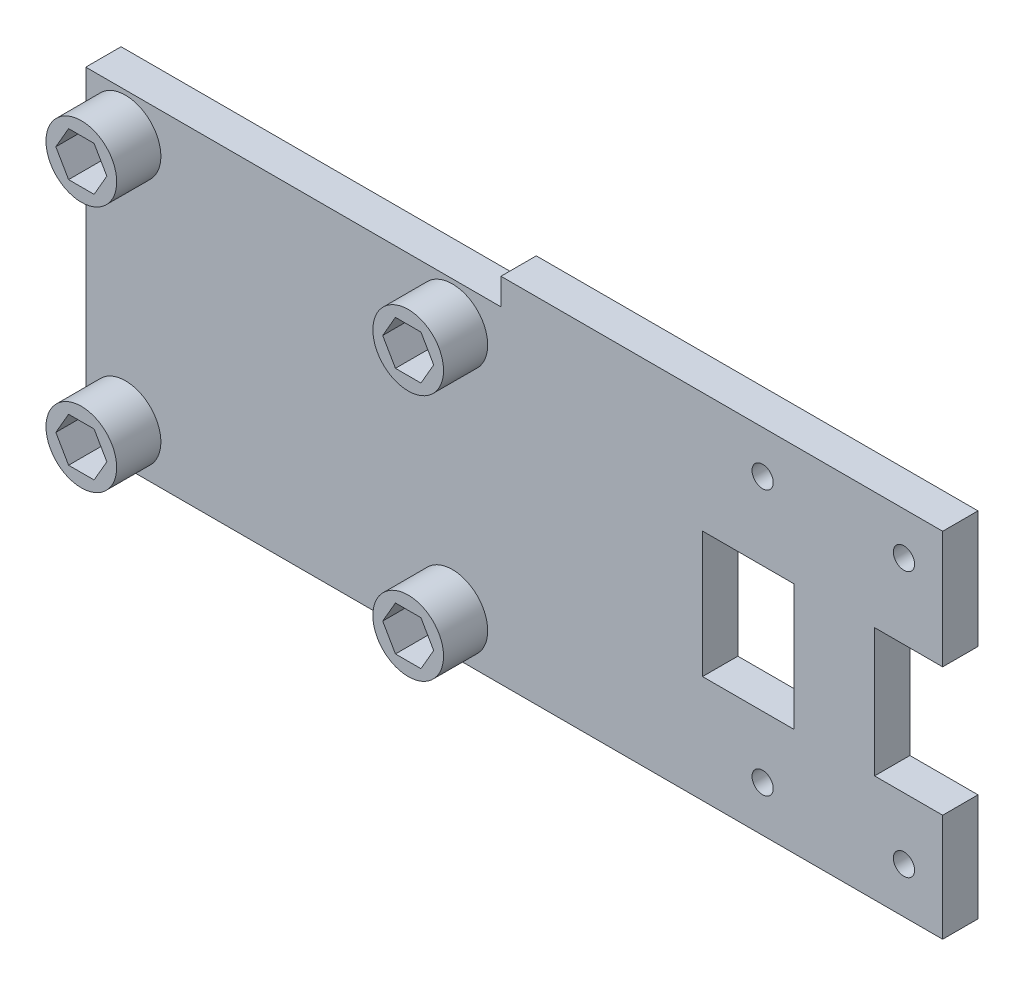
SolidWorks part; units mm, degrees
ref_plane "Front Plane" through (0, 0, 0) normal (0, 0, 1) x (1, 0, 0)
ref_plane "Top Plane" through (0, 0, 0) normal (0, 1, 0) x (1, 0, 0)
ref_plane "Right Plane" through (0, 0, 0) normal (1, 0, 0) x (0, 0, -1)
ref_plane "Plane1" through (0, 0, 34.8116) normal (0, 0, -1) x (-1, 0, 0)
sketch "Sketch1" plane through (0, 0, 34.8116) normal (0, 0, -1) x (-1, 0, 0)
  line L0 (-23.5355, 118.8347) -> (-23.5355, 78.8347)
  line L1 (-23.5355, 78.8347) -> (26.4645, 78.8347)
  line L2 (26.4645, 78.8347) -> (26.4645, 118.8347)
  line L3 (26.4645, 118.8347) -> (-23.5355, 118.8347)
extrude "Boss-Extrude1" add sketch "Sketch1" against normal blind 4
sketch "Sketch2" plane through (0, 0, 38.8116) normal (0, 0, 1) x (1, 0, 0)
  line L0 (23.5355, 90.9981) -> (23.5355, 105.5372)
  line L1 (23.5355, 105.5372) -> (15.8296, 105.5372)
  line L2 (15.8296, 105.5372) -> (15.8296, 90.9981)
  line L3 (15.8296, 90.9981) -> (23.5355, 90.9981)
extrude "Cut-Extrude1" cut sketch "Sketch2" against normal through all
sketch "Sketch3" plane through (0, 0, 38.8116) normal (0, 0, 1) x (1, 0, 0)
  line L0 (6.7257, 105.2654) -> (-3.6465, 105.2654)
  line L1 (-3.6465, 105.2654) -> (-3.6465, 90.9981)
  line L2 (-3.6465, 90.9981) -> (6.7257, 90.9981)
  line L3 (6.7257, 90.9981) -> (6.7257, 105.2654)
extrude "Cut-Extrude2" cut sketch "Sketch3" against normal through all
hole_wizard "CBORE for M2 Pan Head Machine Screw1" positions "Sketch5" profile "Sketch4" counterbore size "M2" standard "ANSI Metric" end condition up to next
sketch "Sketch5" plane through (0, 0, 34.8116) normal (0, 0, -1) x (-1, 0, 0)
  point P0 (-3.1566, 84.0163)
  point P1 (-19.1566, 84.0163)
  point P2 (-19.1566, 114.0163)
  point P3 (-3.1566, 114.0163)
sketch "Sketch4" plane through (3.1566, 84.0163, 34.8116) normal (1, 0, 0) x (0, 1, 0)
  line L0 (0, 0) -> (0, 4)
  line L1 (0, 4) -> (1.2, 4)
  line L3 (1.2, 4) -> (1.2, 1.6)
  line L4 (1.2, 1.6) -> (2.5, 1.6)
  line L5 (2.5, 1.6) -> (2.5, 0)
  line L7 (2.5, 0) -> (0, 0)
  line L11 (0, -6.35) -> (0, 107.95) construction
  dimension "Thru Hole Dia." = 2.4
  dimension "Thru Hole Depth" = 4
  dimension "C'Bore Dia." = 5
  dimension "C'Bore Depth" = 1.6
sketch "Sketch6" plane through (0, 0, 38.8116) normal (0, 0, 1) x (1, 0, 0)
  line L1 (-26.4645, 78.8347) -> (-73.4645, 78.8347)
  line L2 (-26.4645, 78.8347) -> (-26.4645, 115.8347)
  line L3 (-26.4645, 115.8347) -> (-73.4645, 115.8347)
  line L4 (-73.4645, 78.8347) -> (-73.4645, 115.8347)
  dimension "D1" = 47
  dimension "D2" = 37
extrude "Boss-Extrude2" add sketch "Sketch6" against normal up to surface (4 mm away) up to face at (0.6566, 84.0163, 34.8116)
sketch "Sketch7" plane through (0, 0, 38.8116) normal (0, 0, 1) x (1, 0, 0)
  line L0 (-68.9645, 111.3347) -> (-68.9645, 83.3347) construction
  line L1 (-73.4645, 97.3347) -> (-68.9645, 97.3347) construction
  line L2 (-73.4645, 115.8347) -> (-73.4645, 78.8347) construction
  line L3 (-26.4645, 115.8347) -> (-26.4645, 118.8347) construction
  circle A0 centre (-68.9645, 111.3347) radius 4
  circle A1 centre (-31.9645, 111.3347) radius 4
  circle A2 centre (-68.9645, 83.3347) radius 4
  circle A3 centre (-31.9645, 83.3347) radius 4
  dimension "D3" = 8
  dimension "D1" = 37
  dimension "D2" = 28
  dimension "D4" = 5.5
extrude "Boss-Extrude3" add sketch "Sketch7" along normal blind 5
hole_wizard "Ø2.7 (2.7) Diameter Hole1" positions "Sketch8" profile "Sketch9" hole size "Ø2.7" standard "ANSI Metric"
sketch "Sketch8" plane through (0, 0, 43.8116) normal (0, 0, 1) x (1, 0, 0)
  point P0 (-68.9645, 111.3347)
  point P3 (-31.9645, 111.3347)
  point P6 (-31.9645, 83.3347)
  point P9 (-68.9645, 83.3347)
sketch "Sketch9" plane through (-68.9645, 111.3347, 43.8116) normal (1, 0, 0) x (0, -1, 0)
  line L0 (0, 0) -> (0, 4.8112)
  line L1 (0, 4.8112) -> (1.35, 4)
  line L2 (1.35, 4) -> (1.35, 0)
  line L5 (1.35, 0) -> (0, 0)
  line L10 (0, 4.8112) -> (-1.35, 4) construction
  line L11 (0, -6.35) -> (0, 107.95) construction
  dimension "Hole Dia." = 2.7
  dimension "Hole Depth" = 4
  dimension "Drill Angle" = 118
sketch "Sketch10" plane through (0, 0, 43.8116) normal (0, 0, 1) x (1, 0, 0)
  line L0 (-26.4645, 115.8347) -> (-73.4645, 115.8347) construction
  line L1 (-67.5211, 113.8347) -> (-70.4078, 113.8347)
  line L2 (-70.4078, 113.8347) -> (-71.8512, 111.3347)
  line L3 (-71.8512, 111.3347) -> (-70.4078, 108.8347)
  line L4 (-70.4078, 108.8347) -> (-67.5211, 108.8347)
  line L5 (-67.5211, 108.8347) -> (-66.0777, 111.3347)
  line L6 (-66.0777, 111.3347) -> (-67.5211, 113.8347)
  line L8 (-67.5211, 85.8347) -> (-70.4078, 85.8347)
  line L9 (-70.4078, 85.8347) -> (-71.8512, 83.3347)
  line L10 (-71.8512, 83.3347) -> (-70.4078, 80.8347)
  line L11 (-70.4078, 80.8347) -> (-67.5211, 80.8347)
  line L12 (-67.5211, 80.8347) -> (-66.0777, 83.3347)
  line L13 (-66.0777, 83.3347) -> (-67.5211, 85.8347)
  line L14 (-30.5211, 113.8347) -> (-33.4078, 113.8347)
  line L15 (-33.4078, 113.8347) -> (-34.8512, 111.3347)
  line L16 (-34.8512, 111.3347) -> (-33.4078, 108.8347)
  line L17 (-33.4078, 108.8347) -> (-30.5211, 108.8347)
  line L18 (-30.5211, 108.8347) -> (-29.0777, 111.3347)
  line L19 (-29.0777, 111.3347) -> (-30.5211, 113.8347)
  line L20 (-30.5211, 85.8347) -> (-33.4078, 85.8347)
  line L21 (-33.4078, 85.8347) -> (-34.8512, 83.3347)
  line L22 (-34.8512, 83.3347) -> (-33.4078, 80.8347)
  line L23 (-33.4078, 80.8347) -> (-30.5211, 80.8347)
  line L24 (-30.5211, 80.8347) -> (-29.0777, 83.3347)
  line L25 (-29.0777, 83.3347) -> (-30.5211, 85.8347)
  circle A0 centre (-68.9645, 111.3347) radius 2.5 construction
  circle A1 centre (-68.9645, 83.3347) radius 2.5 construction
  circle A2 centre (-31.9645, 111.3347) radius 2.5 construction
  circle A3 centre (-31.9645, 83.3347) radius 2.5 construction
  dimension "D1" = 5
extrude "Cut-Extrude3" cut sketch "Sketch10" against normal blind 6.5
